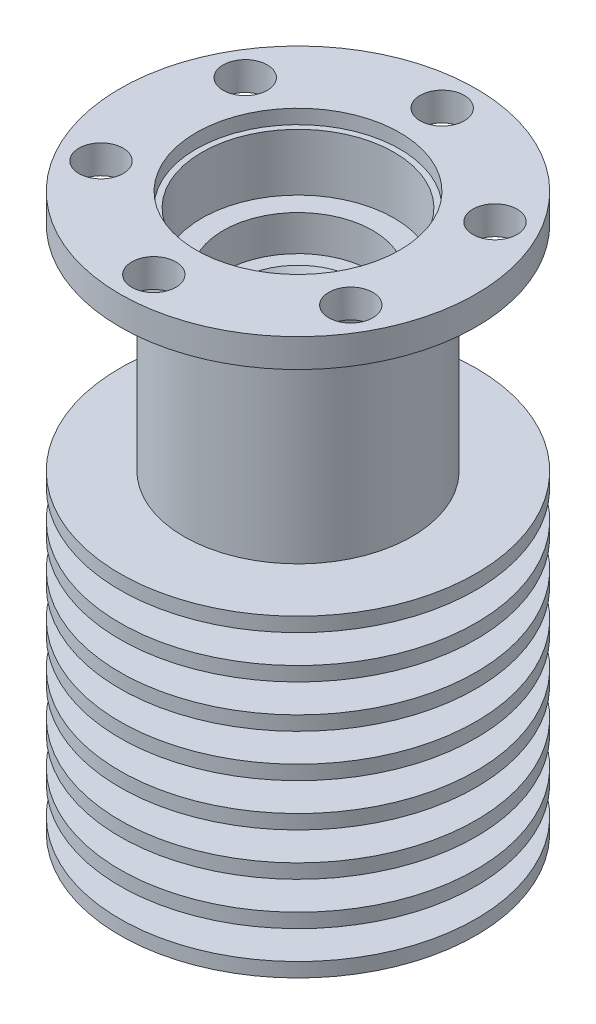
SolidWorks part; units mm, degrees
material "aluminio"
ref_plane "Alzado" through (0, 0, 0) normal (0, 0, 1) x (1, 0, 0)
ref_plane "Planta" through (0, 0, 0) normal (0, 1, 0) x (1, 0, 0)
ref_plane "Vista lateral" through (0, 0, 0) normal (1, 0, 0) x (0, 0, -1)
sketch "Croquis1" plane through (0, 0, 0) normal (0, 0, 1) x (1, 0, 0)
  line L0 (0, 0) -> (6, 0)
  line L1 (6, 0) -> (6, 9)
  line L2 (6, 9) -> (5.25, 9)
  line L3 (5.25, 9) -> (5.25, 12)
  line L4 (5.25, 12) -> (4.75, 12)
  line L5 (4.75, 12) -> (4.75, 22)
  line L6 (8, 37) -> (12.5, 37)
  line L7 (0, 39) -> (0, 0)
  line L8 (12.5, 37) -> (12.5, 39)
  line L9 (12.5, 39) -> (0, 39)
  line L12 (4.75, 22) -> (8, 22)
  line L13 (8, 22) -> (8, 37)
  line L19 (0, 39) -> (0, 0) construction
  dimension "D1" = 9
  dimension "D2" = 3
  dimension "D3" = 10
  dimension "D4" = 2
  dimension "D5" = 12.5
  dimension "D7" = 15
  dimension "D8" = 6
  dimension "D9" = 5.25
  dimension "D10" = 4.75
  dimension "D14" = 8
revolve "Revolución1" add sketch "Croquis1" angle 360 about L19
sketch "Croquis2" plane through (0, 0, 0) normal (0, 0, 1) x (1, 0, 0)
  line L0 (0, 0) -> (0, 39) construction
  line L2 (0, 0) -> (2.5, 0)
  line L3 (2.5, 0) -> (2.5, 9)
  line L4 (2.5, 9) -> (1.7, 9)
  line L5 (1.7, 9) -> (1.7, 11)
  line L6 (1.7, 11) -> (3.25, 11)
  line L7 (3.25, 11) -> (3.25, 31.5)
  line L8 (3.25, 31.5) -> (5.25, 31.5)
  line L9 (5.25, 31.5) -> (5.25, 34)
  line L10 (12.5, 39) -> (-12.5, 39) construction
  line L11 (0, 39) -> (6.75, 39)
  line L12 (5.25, 34) -> (6.75, 34)
  line L13 (6.75, 34) -> (6.75, 39)
  line L14 (0, 39) -> (0, 0)
  dimension "D1" = 9
  dimension "D2" = 2
  dimension "D3" = 5
  dimension "D5" = 2.5
  dimension "D6" = 13.5
  dimension "D8" = 10.5
  dimension "D9" = 6.5
  dimension "D10" = 3.4
  dimension "D11" = 5
revolve "Cortar-Revolución1" cut sketch "Croquis2" angle 360 about L0
cosmetic thread "Rosca cosmética1" parameters "D1"=7, "D2"=6
sketch "Croquis3" plane through (0, 0, 0) normal (0, -1, 0) x (1, 0, 0)
  circle A0 centre (0, 0) radius 3.25
  circle A1 centre (0, 0) radius 12.5
  dimension "D1" = 25
  dimension "D2" = 6.5
extrude "Saliente-Extruir1" add sketch "Croquis3" against normal blind 1
sketch "Croquis4" plane through (0, 0, 0) normal (0, 0, 1) x (1, 0, 0)
  line L0 (0, 0) -> (0, 36.9563) construction
pattern_linear "MatrizL1" count 8 spacing 3 along (0, 1, 0) of "Saliente-Extruir1"
sketch "Croquis5" plane through (0, 39, 0) normal (0, 1, 0) x (1, 0, 0)
  circle A0 centre (0, 0) radius 10.125 construction
  circle A1 centre (0, 10.125) radius 1.55
  dimension "D1" = 20.25
  dimension "D2" = 3.1
extrude "Cortar-Extruir1" cut sketch "Croquis5" against normal up to next
pattern_circular "MatrizC1" count 6 over 360 about axis through (0, 0, 0) along (0, 1, 0) of "Cortar-Extruir1"
chamfer "Chaflán3" distance 0.3 angle 60 1 edges at (0, 11, -1.7)
sketch "Croquis6" plane through (0, 39, 0) normal (0, 1, 0) x (1, 0, 0)
  circle A0 centre (0, 0) radius 7.15
  dimension "D1" = 14.3
extrude "Cortar-Extruir2" cut sketch "Croquis6" against normal blind 1
chamfer "Chaflán2" distance 0.15 angle 60 1 edges at (0, 9, -1.7)
chamfer "Chaflán4" distance 1 angle 60 1 edges at (0, 31.5, -3.25)
